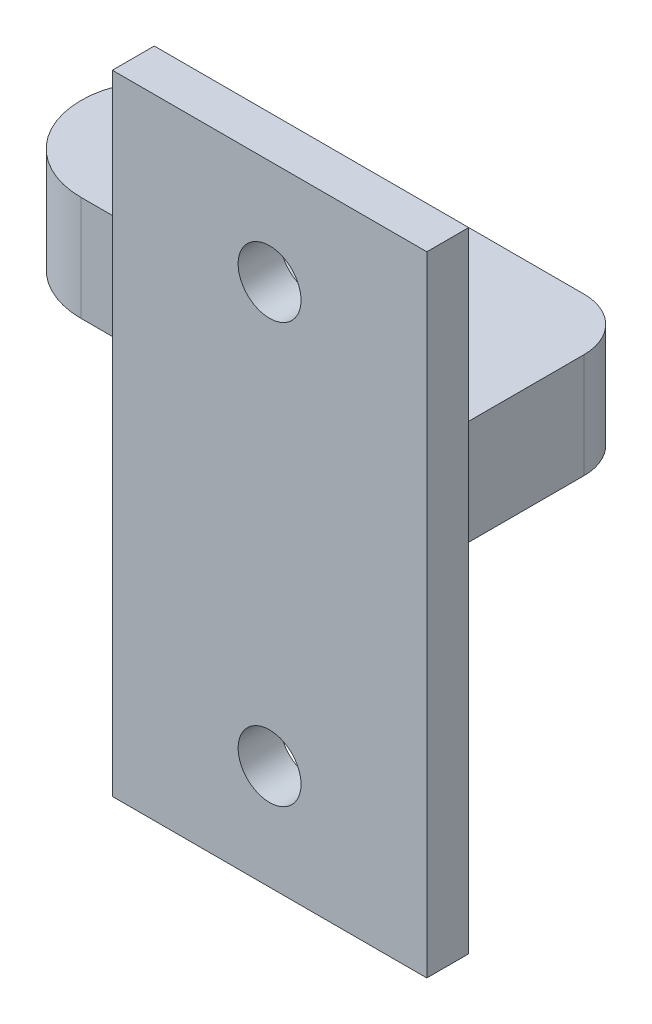
SolidWorks part; units mm, degrees
ref_plane "Front Plane" through (0, 0, 0) normal (0, 0, 1) x (1, 0, 0)
ref_plane "Top Plane" through (0, 0, 0) normal (0, 1, 0) x (1, 0, 0)
ref_plane "Right Plane" through (0, 0, 0) normal (1, 0, 0) x (0, 0, -1)
sketch "Sketch1" plane through (0, 0, 0) normal (0, 0, 1) x (1, 0, 0)
  line L1 (-7.5, 15) -> (7.5, 15)
  line L2 (-7.5, 15) -> (-7.5, -15)
  line L3 (-7.5, -15) -> (7.5, -15)
  line L4 (7.5, 15) -> (7.5, -15)
  line L5 (-7.5, 15) -> (7.5, -15) construction
  line L6 (-7.5, -15) -> (7.5, 15) construction
  circle A0 centre (0, 10) radius 1.5
  circle A1 centre (0, -10) radius 1.5
  point P4 (0, 0)
  dimension "D1" = 3
  dimension "D2" = 3
  dimension "D3" = 10
  dimension "D4" = 10
  dimension "D5" = 15
  dimension "D6" = 30
extrude "Boss-Extrude1" add sketch "Sketch1" along normal blind 2
sketch "Sketch2" plane through (0, 0, 0) normal (0, 1, 0) x (1, 0, 0)
  line L0 (7.5, 0) -> (-7.5, 0) construction
  line L1 (-3, 0) -> (3, 0)
  line L2 (-7.5, 4.5) -> (-15.5, 4.5)
  line L4 (-15.5, 12.5) -> (0.5, 12.5)
  line L5 (3, 10) -> (3, 0)
  arc A0 (-3, 0) -> (-7.5, 4.5) centre (-7.5, 0) ccw
  arc A2 (3, 10) -> (0.5, 12.5) centre (0.5, 10) ccw
  arc A3 (-15.5, 12.5) -> (-15.5, 4.5) centre (-15.5, 8.5) ccw
  circle A4 centre (-15.5, 8.5) radius 1.5
  dimension "D4" = 5
  dimension "D3" = 8
  dimension "D6" = 3
  dimension "D1" = 3
  dimension "D2" = 3
  dimension "D5" = 8
extrude "Boss-Extrude2" add sketch "Sketch2" along normal mid plane 5
